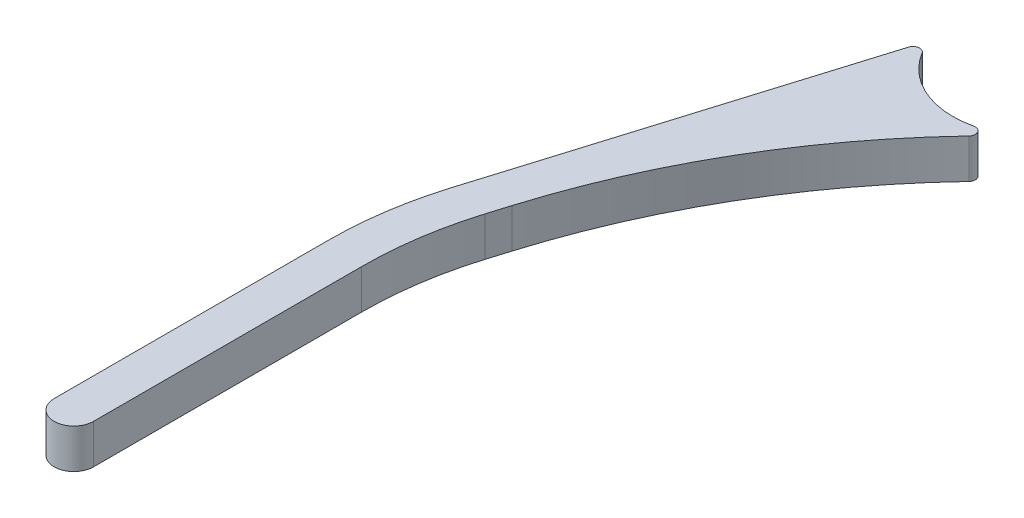
SolidWorks part; units mm, degrees
material "Pine"
ref_plane "Front Plane" through (0, 0, 0) normal (0, 0, 1) x (1, 0, 0)
ref_plane "Top Plane" through (0, 0, 0) normal (0, 1, 0) x (1, 0, 0)
ref_plane "Right Plane" through (0, 0, 0) normal (1, 0, 0) x (0, 0, -1)
sketch "Sketch1" plane through (0, 0, 0) normal (0, 1, 0) x (1, 0, 0)
  line L2 (-99.0206, -242.4276) -> (-99.0206, -374.65)
  line L5 (-99.0206, -374.65) -> (-79.9706, -374.65) construction
  line L8 (-79.9706, -245.2669) -> (-79.9706, -374.65)
  line L11 (-91.2929, -190.5791) -> (-39.6864, -21.3006)
  line L13 (-69.1617, -183.3118) -> (-72.2429, -193.4184)
  line L14 (-79.9706, -218.7668) -> (-98.1926, -213.2116) construction
  line L15 (27.0899, -29.0041) -> (41.0118, -16.0009) construction
  arc A4 (-79.9706, -374.65) -> (-99.0206, -374.65) centre (-89.4956, -374.65) cw
  arc A7 (-33.9346, -20.5801) -> (9.0253, -38.6477) centre (0, 0) ccw
  arc A8 (-91.2929, -190.5791) -> (-99.0206, -242.4276) centre (78.7794, -242.4276) ccw
  arc A9 (-72.2429, -193.4184) -> (-79.9706, -245.2669) centre (97.8294, -245.2669) ccw
  arc A10 (-39.6864, -21.3006) -> (-33.9346, -20.5801) centre (-36.6494, -22.2265) cw
  arc A11 (-69.1617, -183.3118) -> (12.0504, -43.925) centre (266.9062, -285.7659) cw
  arc A12 (9.0253, -38.6477) -> (12.0504, -43.925) centre (9.7473, -41.7395) cw
  circle A13 centre (0, 0) radius 37.465 construction
  circle A14 centre (0, 0) radius 31.75 construction
  dimension "D5" = 3.175
  dimension "D3" = 39.6875
  dimension "D4" = 30
  dimension "D7" = 74.93
  dimension "D8" = 63.5
  dimension "D9" = 374.65
  dimension "D11" = 177.8
  dimension "D1" = 19.05
  dimension "D2" = 163.046
  dimension "D10" = 89.4956
extrude "Boss-Extrude1" add sketch "Sketch1" along normal blind 19.05
ref_plane "Plane1" through (-89.4956, 19.05, 384.175) normal (0, 0, 1) x (1, 0, 0)
hole_wizard "1/8 (0.125) Diameter Hole1" positions "Sketch2" profile "Sketch3" hole size "1/8" standard "ANSI Inch"
sketch "Sketch2" plane through (0, 0, 0) normal (0, -1, 0) x (-1, 0, 0)
  line L1 (87.553, -217.6366) -> (89.4956, -358.775) construction
  line L9 (31.1926, -50.114) -> (0, 0) construction
  line L14 (78.028, -219.0563) -> (97.078, -216.217) construction
  line L16 (99.0206, -358.775) -> (79.9706, -358.775) construction
  line L17 (99.0206, -242.4276) -> (99.0206, -374.65) construction
  line L18 (79.9706, -374.65) -> (79.9706, -245.2669) construction
  line L19 (46.2578, -42.8559) -> (4.686, -62.8844) construction
  line L20 (39.6864, -21.3006) -> (91.2929, -190.5791) construction
  line L21 (0, 0) -> (25.4719, -52.8701) construction
  line L23 (25.4719, -52.8701) -> (87.553, -217.6366) construction
  arc A0 (79.9706, -245.2669) -> (72.2429, -193.4184) centre (-97.8294, -245.2669) ccw construction
  arc A1 (99.0206, -242.4276) -> (91.2929, -190.5791) centre (-78.7794, -242.4276) ccw construction
  arc A2 (79.9706, -374.65) -> (99.0206, -374.65) centre (89.4956, -374.65) ccw construction
  arc A4 (69.1617, -183.3118) -> (-12.0504, -43.925) centre (-266.9062, -285.7659) ccw construction
  arc A5 (-9.0253, -38.6477) -> (33.9346, -20.5801) centre (0, 0) ccw construction
  point P0 (89.4956, -358.775)
  point P2 (31.1926, -50.114)
  point P4 (87.553, -217.6366)
  point P68 (89.4956, -358.775)
  point P72 (89.4956, -384.175)
  point P92 (15.386, -36.5837)
  point P98 (30.9714, -50.2206)
  point P99 (0, 0)
  dimension "D1" = 25.4
  dimension "D2" = 19.05
  dimension "D3" = 6.35
sketch "Sketch3" plane through (-89.4956, 0, 358.775) normal (1, 0, 0) x (0, 0, -1)
  line L0 (0, 0) -> (0, 12.0791)
  line L1 (0, 12.0791) -> (1.5875, 11.1252)
  line L2 (1.5875, 11.1252) -> (1.5875, 0)
  line L5 (1.5875, 0) -> (0, 0)
  line L10 (0, 12.0791) -> (-1.5875, 11.1252) construction
  line L11 (0, -6.35) -> (0, 107.95) construction
  dimension "Hole Dia." = 3.175
  dimension "Hole Depth" = 11.1252
  dimension "Drill Angle" = 118
